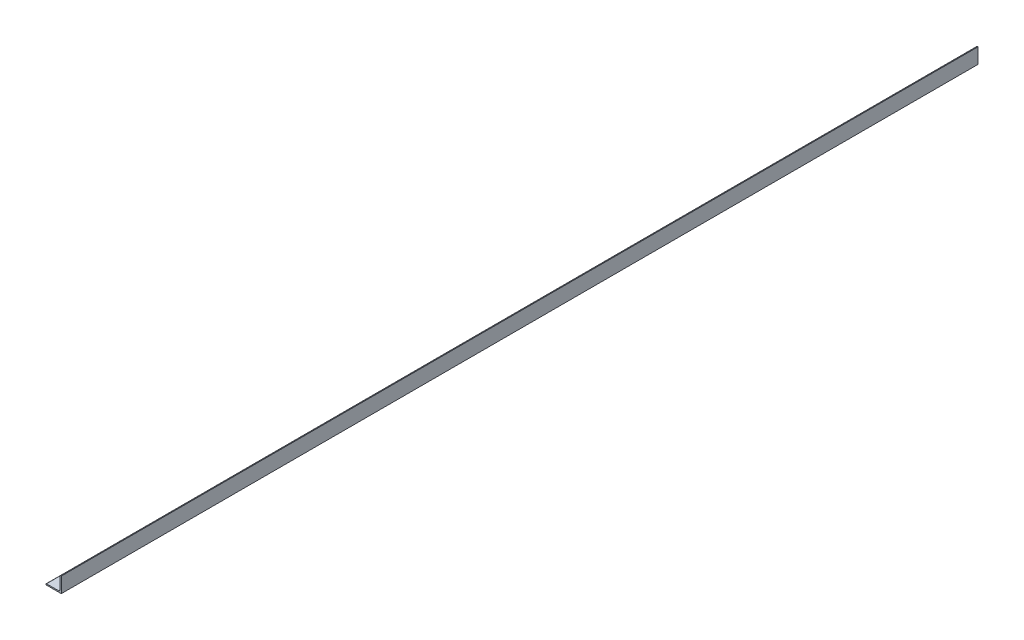
SolidWorks part; units mm, degrees
material "AISI 304"
ref_plane "Спереди" through (0, 0, 0) normal (0, 0, 1) x (1, 0, 0)
ref_plane "Сверху" through (0, 0, 0) normal (0, 1, 0) x (1, 0, 0)
ref_plane "Справа" through (0, 0, 0) normal (1, 0, 0) x (0, 0, -1)
sketch "Эскиз1" plane through (0, 0, 0) normal (0, 0, -1) x (-1, 0, 0)
  line L0 (0, 0) -> (0, 50)
  line L1 (0, 50) -> (2.2, 50)
  line L2 (4, 48.2) -> (4, 9.5)
  line L3 (9.5, 4) -> (48.2, 4)
  line L4 (50, 2.2) -> (50, 0)
  line L5 (50, 0) -> (0, 0)
  arc A0 (4, 9.5) -> (9.5, 4) centre (9.5, 9.5) ccw
  arc A1 (2.2, 50) -> (4, 48.2) centre (2.2, 48.2) cw
  arc A2 (48.2, 4) -> (50, 2.2) centre (48.2, 2.2) cw
  point P11 (4, 50)
  point P14 (50, 4)
  dimension "D5" = 5.5
  dimension "D6" = 1.8
  dimension "D1" = 50
  dimension "D2" = 50
  dimension "D3" = 4
  dimension "D4" = 4
extrude "Бобышка-Вытянуть1" add sketch "Эскиз1" along normal mid plane 3000
sketch "Эскиз2" plane through (0, 0, 0) normal (0, -1, 0) x (1, 0, 0)
  line L0 (-26.5, 1500) -> (-26.5, -1500) construction
  line L1 (-50, -1500) -> (-50, 1500) construction
  line L2 (0, -1500) -> (-50, -1500) construction
  line L3 (0, 1500) -> (-50, 1500) construction
  circle A0 centre (-26.5, 1400) radius 4.5
  circle A1 centre (-26.5, 1000) radius 4.5
  circle A2 centre (-26.5, 600) radius 4.5
  circle A3 centre (-26.5, 200) radius 4.5
  circle A4 centre (-26.5, -200) radius 4.5
  circle A5 centre (-26.5, -600) radius 4.5
  circle A6 centre (-26.5, -1000) radius 4.5
  circle A7 centre (-26.5, -1400) radius 4.5
  dimension "D2" = 9
  dimension "D1" = 23.5
  dimension "D3" = 100
  dimension "D5" = 400
  dimension "D4" = 8
extrude "Вырез-Вытянуть1" [suppressed] cut sketch "Эскиз2" against normal through all
sketch "Эскиз3" plane through (-4, 0, 0) normal (-1, 0, 0) x (0, 0, 1)
  line L0 (1500, 18) -> (-1500, 18) construction
  line L1 (1500, 9.5) -> (1500, 48.2) construction
  line L2 (-1500, 9.5) -> (-1500, 48.2) construction
  circle A0 centre (220, 18) radius 4.5
  circle A1 centre (-710, 18) radius 4.5
  circle A2 centre (-1330, 18) radius 4.5
  circle A4 centre (160, 18) radius 4.5
  circle A5 centre (-650, 18) radius 4.5
  circle A6 centre (-1270, 18) radius 4.5
  circle A7 centre (780, 18) radius 4.5
  circle A8 centre (840, 18) radius 4.5
  dimension "D1" = 60
  dimension "D6" = 60
  dimension "D10" = 9
  dimension "D5" = 60
  dimension "D2" = 170
  dimension "D3" = 810
  dimension "D4" = 60
  dimension "D7" = 560
  dimension "D8" = 560
  dimension "D9" = 18
extrude "Вырез-Вытянуть2" [suppressed] cut sketch "Эскиз3" against normal through all both and the other way through all
